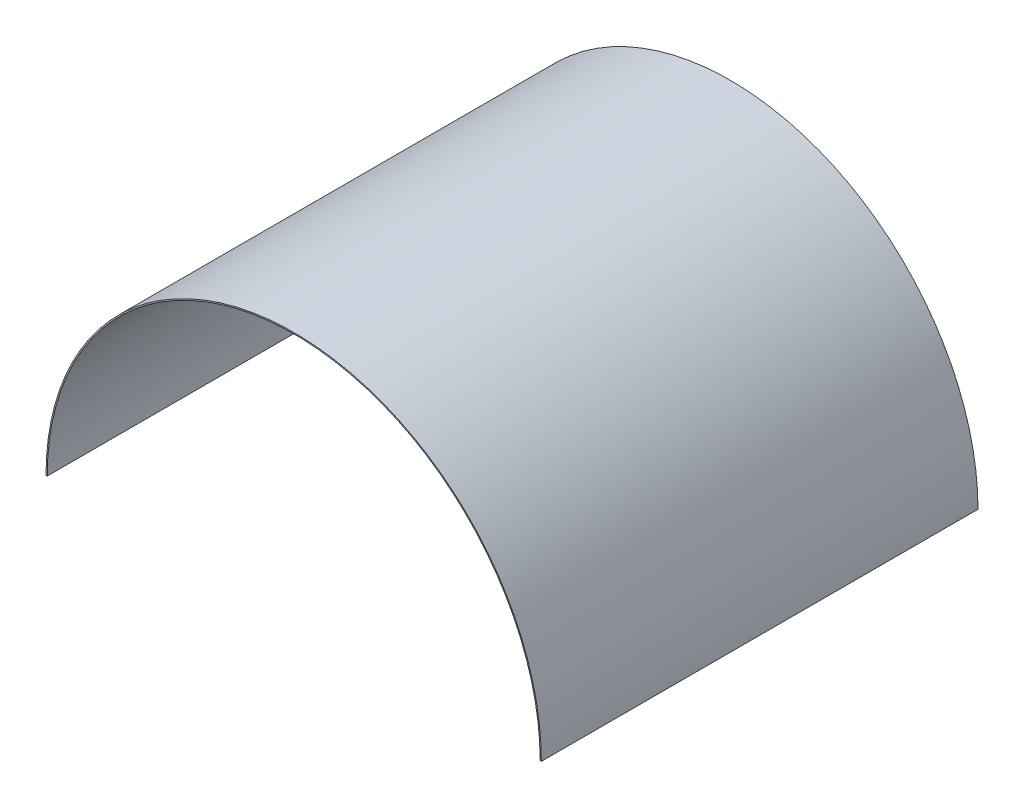
SolidWorks part; units mm, degrees
material "ABS"
ref_plane "Front Plane" through (0, 0, 0) normal (0, 0, 1) x (1, 0, 0)
ref_plane "Top Plane" through (0, 0, 0) normal (0, 1, 0) x (1, 0, 0)
ref_plane "Right Plane" through (0, 0, 0) normal (1, 0, 0) x (0, 0, -1)
sketch "Sketch1" plane through (0, 0, 0) normal (0, 0, 1) x (1, 0, 0)
  arc A0 (203.2, 0) -> (-203.2, 0) centre (0, 0) ccw
  dimension "D1" = 406.4
extrude "Extrude-Thin1" add sketch "Sketch1" along normal blind 360 thin contours A0
